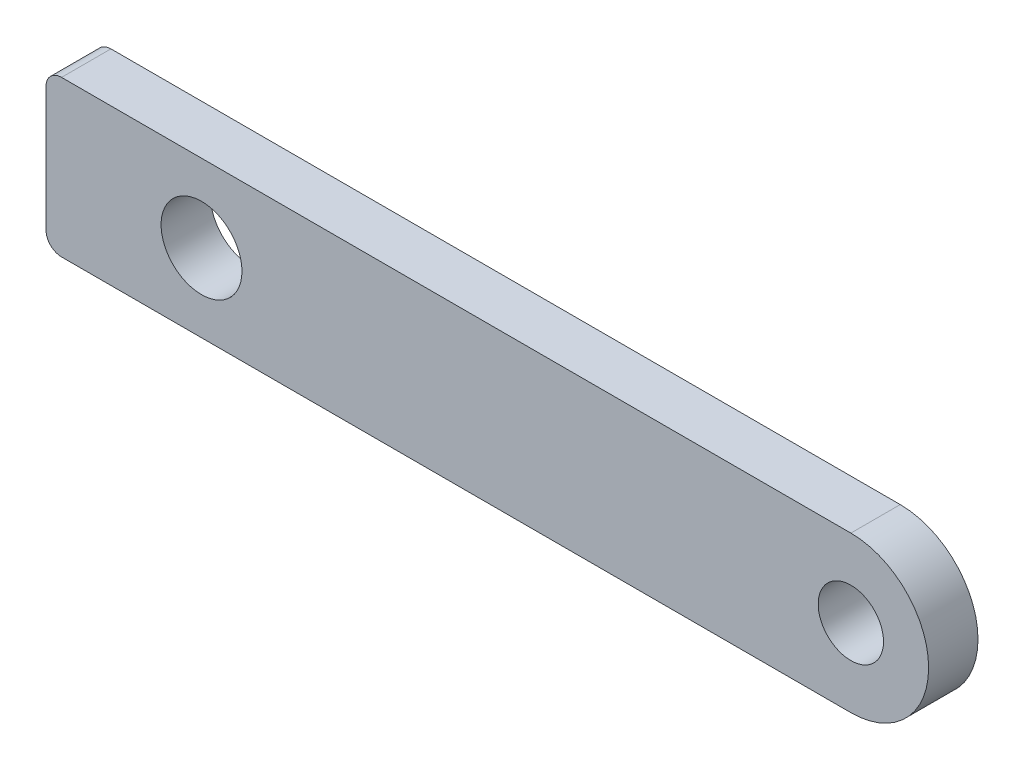
SolidWorks part; units mm, degrees
ref_plane "Front Plane" through (0, 0, 0) normal (0, 0, 1) x (1, 0, 0)
ref_plane "Top Plane" through (0, 0, 0) normal (0, 1, 0) x (1, 0, 0)
ref_plane "Right Plane" through (0, 0, 0) normal (1, 0, 0) x (0, 0, -1)
ref_plane "Plane1" through (0, 0, 3.175) normal (0, 0, 1) x (1, 0, 0)
sketch "Sketch1" plane through (0, 0, 3.175) normal (0, 0, 1) x (1, 0, 0)
  line L0 (0, 9) -> (0, 1)
  line L1 (1, 0) -> (51.75, 0)
  line L2 (51.75, 10) -> (1, 10)
  arc A0 (1, 10) -> (0, 9) centre (1, 9) ccw
  arc A1 (0, 1) -> (1, 0) centre (1, 1) ccw
  arc A2 (51.75, 0) -> (51.75, 10) centre (51.75, 5) ccw
extrude "Boss-Extrude1" add sketch "Sketch1" against normal blind 3.175
hole_wizard "Ø4.2 (4.2) Diameter Hole1" positions "Sketch3" profile "Sketch2" hole size "Ø4.2" standard "ANSI Metric"
sketch "Sketch3" plane through (0, 0, 3.175) normal (0, 0, 1) x (1, 0, 0)
  point P0 (51.75, 5)
sketch "Sketch2" plane through (51.75, 5, 3.175) normal (1, 0, 0) x (0, -1, 0)
  line L0 (0, 0) -> (0, 3.175)
  line L1 (0, 3.175) -> (2.1, 3.175)
  line L2 (2.1, 3.175) -> (2.1, 0)
  line L5 (2.1, 0) -> (0, 0)
  line L11 (0, -6.35) -> (0, 107.95) construction
  dimension "Thru Hole Dia." = 4.2
  dimension "Thru Hole Depth" = 3.175
hole_wizard "Ø5.2 (5.2) Diameter Hole1" positions "Sketch5" profile "Sketch4" hole size "Ø5.2" standard "ANSI Metric"
sketch "Sketch5" plane through (0, 0, 3.175) normal (0, 0, 1) x (1, 0, 0)
  point P0 (10, 5)
sketch "Sketch4" plane through (10, 5, 3.175) normal (1, 0, 0) x (0, -1, 0)
  line L0 (0, 0) -> (0, 3.175)
  line L1 (0, 3.175) -> (2.6, 3.175)
  line L2 (2.6, 3.175) -> (2.6, 0)
  line L5 (2.6, 0) -> (0, 0)
  line L11 (0, -6.35) -> (0, 107.95) construction
  dimension "Thru Hole Dia." = 5.2
  dimension "Thru Hole Depth" = 3.175
